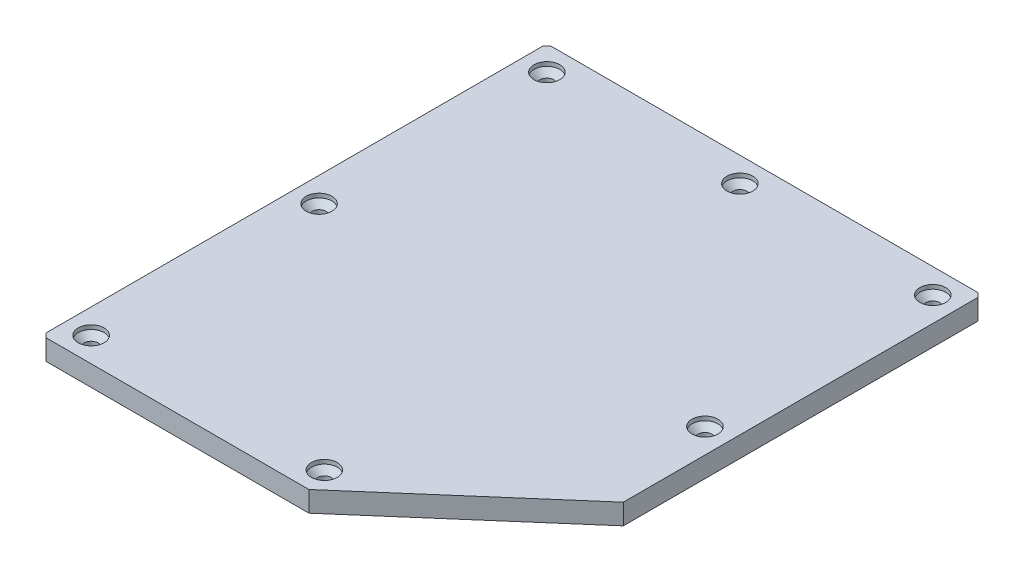
SolidWorks part; units mm, degrees
ref_plane "Front Plane" through (0, 0, 0) normal (0, 0, 1) x (1, 0, 0)
ref_plane "Top Plane" through (0, 0, 0) normal (0, 1, 0) x (1, 0, 0)
ref_plane "Right Plane" through (0, 0, 0) normal (1, 0, 0) x (0, 0, -1)
sketch "block_perimeter" plane through (0, 0, 0) normal (0, 1, 0) x (1, 0, 0)
  line L8 (52, 60.5) -> (-52, 60.5)
  line L10 (53, -26.8945) -> (53, 59.5)
  line L11 (12.0406, -62.5) -> (53, -26.8945)
  line L12 (-52, -62.5) -> (12.0406, -62.5)
  line L16 (52, 60.5) -> (-52, 60.5)
  line L18 (53, -26.8945) -> (53, 59.5)
  line L19 (12.0406, -62.5) -> (53, -26.8945)
  line L20 (-52, -62.5) -> (12.0406, -62.5)
  line L62 (-53, 59.5) -> (-53, -61.5)
  line L63 (-53, 59.5) -> (-53, -61.5)
  line L234 (53, 59.5) -> (52, 60.5)
  line L235 (53, 59.5) -> (52, 60.5)
  line L236 (-53, -61.5) -> (-52, -62.5)
  line L237 (-53, -61.5) -> (-52, -62.5)
  line L238 (-52, 60.5) -> (-53, 59.5)
  line L239 (-52, 60.5) -> (-53, 59.5)
  dimension "D1" = 0
extrude "Boss-Extrude1" add sketch "block_perimeter" along normal blind 5
sketch "Sketch4" plane through (0, 5, 0) normal (0, 1, 0) x (1, 0, 0)
  line L0 (47, 54.5) -> (-47, 54.5) construction
  point P0 (-47, 54.5)
  point P1 (0, 54.5)
  point P2 (47, 54.5)
  point P5 (47, -1)
  point P6 (-47, -56.5)
  point P7 (9.7973, -56.5)
  point P8 (-47, -1)
hole_wizard "CSK for M3 Countersunk Flat Head Screw1" positions "3DSketch1" profile "Sketch5" countersink size "M3" standard "ISO" end condition through all
sketch3d "3DSketch1"
  point P0 (-47, 5, -54.5)
  point P3 (0, 5, -54.5)
  point P6 (47, 5, -54.5)
  point P9 (47, 5, 1)
  point P12 (9.7973, 5, 56.5)
  point P15 (-47, 5, 56.5)
  point P18 (-47, 5, 1)
sketch "Sketch5" plane through (-47, 5, -54.5) normal (1, 0, 0) x (0, 0, 1)
  line L0 (0, 0) -> (0, 5)
  line L1 (0, 5) -> (1.7, 5)
  line L2 (1.7, 5) -> (1.7, 2.45)
  line L3 (1.7, 2.45) -> (3.15, 1)
  line L4 (3.15, 1) -> (3.15, 0)
  line L6 (3.15, 0) -> (0, 0)
  line L7 (-1.7, 2.45) -> (-3.15, 1) construction
  line L11 (0, -6.35) -> (0, 107.95) construction
  dimension "Thru Hole Dia." = 3.4
  dimension "Thru Hole Depth" = 5
  dimension "C'Sink Dia." = 6.3
  dimension "C'Sink Angle" = 90
  dimension "Head Clearance" = 1
